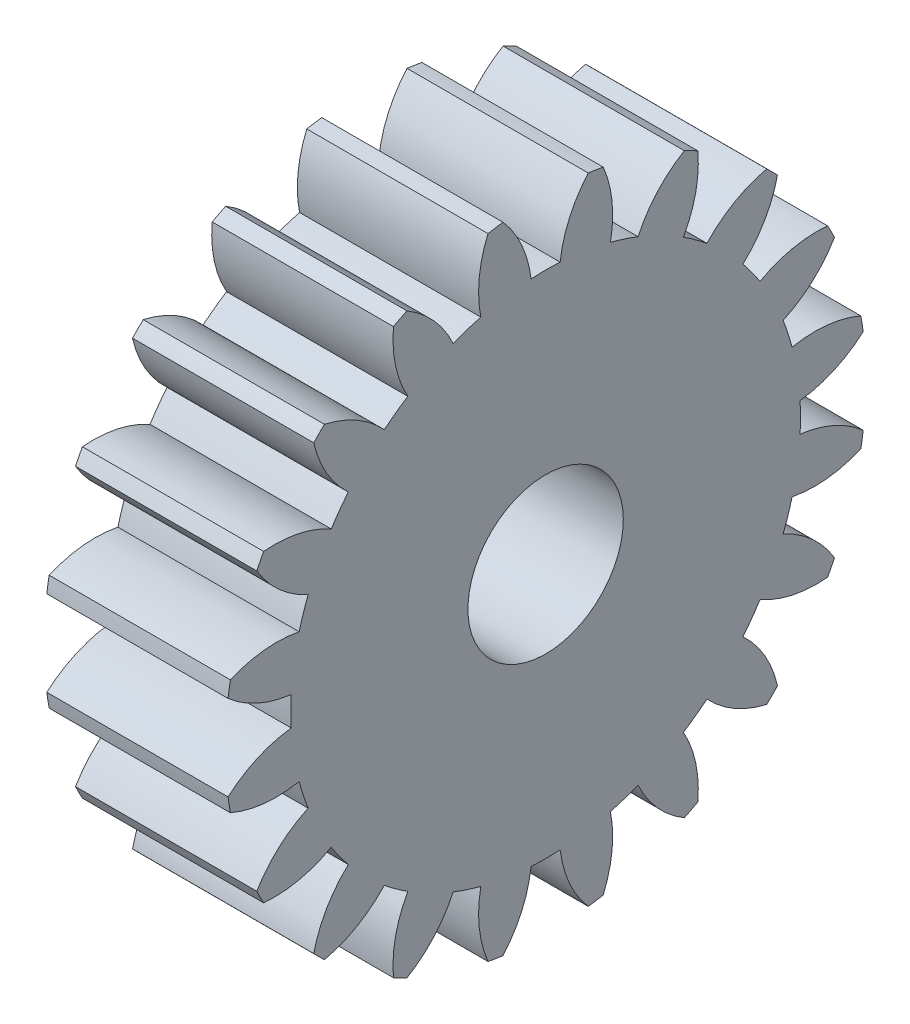
SolidWorks part; units mm, degrees
ref_plane "Plane1" through (0, 0, 0) normal (0, 0, 1) x (1, 0, 0)
ref_plane "Plane2" through (0, 0, 0) normal (0, 1, 0) x (1, 0, 0)
ref_plane "Plane3" through (0, 0, 0) normal (1, 0, 0) x (0, 0, -1)
sketch "HoldingSke" plane through (0, 0, 0) normal (0, 1, 0) x (1, 0, 0)
  line L0 (0, 0) -> (0.8353, -0.304)
  line L1 (-15, 0) -> (100, 0) construction
  line L2 (0, 0) -> (-2.1039, 2.3779)
  line L3 (0, 0) -> (-11.863, 4.5341)
  line L4 (0, 0) -> (8.1152, 2.9537)
  line L5 (0, 0) -> (-46.8476, -17.4728)
  line L6 (0, 0) -> (-4.9738, -3.3558)
  line L7 (-2.1039, 2.3779) -> (8.6586, 51.2059)
  line L8 (-76.2, 54.61) -> (-75.2, 54.61)
  line L9 (-71.009, 38.7566) -> (-53.1078, 45.2721)
  line L10 (-76.2, 71.12) -> (104.1128, 71.12)
  line L11 (0, 0) -> (-6, 0)
  line L12 (-76.2, 101.6) -> (-76.158, 101.6)
  line L13 (24.9733, 27.94) -> (52.9518, 28.4284)
  line L14 (24.9733, 27.94) -> (24.9743, 27.94)
  line L15 (24.9733, 27.94) -> (100.4006, 29.5858)
  line L16 (-63.627, -1.125) -> (-12.827, -1.125)
  circle A0 centre (0, 0) radius 3
  circle A1 centre (0, 0) radius 9.8427
  circle A2 centre (0, 0) radius 37.5
  circle A3 centre (0, 0) radius 3
  dimension "MHD" = 19.6855
  dimension "Hub_dia" = 75
  dimension "Bore" = 6
  dimension "MBD" = 6
  dimension "Num_teeth" = 20
  dimension "Pitch" = 0.8889
  dimension "Overall_len" = 50
  dimension "Show_teeth" = 20
  dimension "Thickness" = 6
  dimension "OAL" = 50.0001
  dimension "T_dim" = 1
  dimension "Ap" = 20
  dimension "H" = 19.05
  dimension "Pitch_radius" = 180.3128
  dimension "Width" = 6
  dimension "Backlash" = 0.042
  dimension "Addendum_fac" = 1
  dimension "Dedendum_fac" = 1.25
  dimension "Clearance_fac" = 0.25
  dimension "Dedendum_add" = 0.001
  dimension "Module" = 1.125
sketch "BasProSke" plane through (0, 0, 0) normal (0, 1, 0) x (1, 0, 0)
  line L0 (-10, 0) -> (60, 0) construction
  line L1 (0, 0) -> (0, 12.375)
  line L2 (0, 0) -> (7, 0)
  line L3 (7, 0) -> (7, 12.375)
  line L4 (7, 12.375) -> (0, 12.375)
  dimension "Thickness" = 7
  dimension "Diameter" = 24.75
revolve "Base-Revolve" add sketch "BasProSke" angle 360 about L0
sketch "TooCutSke" plane through (0, 0, 0) normal (1, 0, 0) x (0, 0, -1)
  line L1 (0, 0) -> (0, 107) construction
  line L2 (0, 0) -> (-0.9561, 11.2093) construction
  line L3 (0, 0) -> (-3.5107, 22.1654) construction
  line L4 (-0.9561, 11.2093) -> (-1.7553, 11.0827) construction
  arc A0 (0.5613, 9.8267) -> (-0.5613, 9.8267) centre (0, 0) ccw
  arc A1 (1.6669, 12.2879) -> (-1.6669, 12.2879) centre (0, 0) ccw
  circle A2 centre (0, 0) radius 11.25 construction
  circle A3 centre (0, 0) radius 10.5715 construction
  arc A4 (-0.5613, 9.8267) -> (-1.6669, 12.2879) centre (-5.0301, 9.2981) ccw
  arc A5 (1.6669, 12.2879) -> (0.5613, 9.8267) centre (5.0301, 9.2981) ccw
  dimension "Root_dia" = 19.6855
  dimension "Overcut_dia" = 24.8008
  dimension "Pitch_dia" = 22.5
  dimension "Base_dia" = 21.1431
  dimension "Flank_rad" = 4.5
  dimension "Half_ang" = 9
  dimension "Half_CT" = 0.8092
extrude "ToothCut" cut sketch "TooCutSke" along normal through all
fillet "Breaks" [suppressed] radius 0.0225
fillet "RootFillets" [suppressed] radius 0.2823
pattern_circular "TeethCuts" count 20 over 360 about axis through (0, 0, 0) along (1, 0, 0) of "ToothCut", "RootFillets", "Breaks"
sketch "HubNeaOneSke" plane through (0, 0, 0) normal (-1, 0, 0) x (0, 0, 1)
  circle A0 centre (0, 0) radius 9.8427
  dimension "Diameter" = 19.6855
extrude "HubNearOne" [suppressed] add sketch "HubNeaOneSke" along normal blind 43.0001
sketch "HubNeaBotSke" plane through (0, 0, 0) normal (-1, 0, 0) x (0, 0, 1)
  circle A0 centre (0, 0) radius 9.8427
  dimension "Diameter" = 19.6855
extrude "HubNearBoth" [suppressed] add sketch "HubNeaBotSke" along normal blind 21.5
ref_plane "FarPln" through (7, 0, 0) normal (1, 0, 0) x (0, 0, -1)
sketch "HubFarSke" plane through (7, 0, 0) normal (1, 0, 0) x (0, 0, -1)
  circle A0 centre (0, 0) radius 9.8427
  dimension "Diameter" = 19.6855
extrude "HubFar" [suppressed] add sketch "HubFarSke" along normal blind 21.5
sketch "BorSke" plane through (0, 0, 0) normal (1, 0, 0) x (0, 0, -1)
  circle A0 centre (0, 0) radius 3
  dimension "Diameter" = 6
extrude "Bore" cut sketch "BorSke" along normal mid plane 100.0001
sketch "KeySke" plane through (0, 0, 0) normal (1, 0, 0) x (0, 0, -1)
  line L0 (-1, 0) -> (-1, 4)
  line L1 (-1, 4) -> (1, 4)
  line L2 (1, 4) -> (1, 0)
  line L3 (0, 0) -> (0, 34) construction
  line L4 (-1, 0) -> (1, 0)
  dimension "Offset" = 4
  dimension "Width" = 2
extrude "Keyway" [suppressed] cut sketch "KeySke" along normal mid plane 100.0001
pattern_circular "Keyway2" [suppressed] count 2 every 90 about axis through (-10, 0, 0) along (1, 0, 0)
sketch "Sketch1" plane through (7, 0, 0) normal (1, 0, 0) x (0, 0, -1)
  circle A0 centre (0, 0) radius 3 construction
  circle A1 centre (0, 0) radius 3
extrude "Boss-Extrude1" add sketch "Sketch1" against normal up to surface (7 mm away) up to face at (0, 0, -3)
sketch "Sketch2" plane through (7, 0, 0) normal (1, 0, 0) x (0, 0, -1)
  line L0 (-1.8, 2.0125) -> (-1.8, -2.0125)
  line L1 (1.8, 2.0125) -> (1.8, -2.0125)
  line L2 (-1.8, 0) -> (1.8, 0) construction
  circle A0 centre (0, 0) radius 2.7
  point P9 (0, 0)
  dimension "D1" = 5.4
  dimension "D2" = 3.6
extrude "Cut-Extrude1" cut sketch "Sketch2" against normal up to surface (7 mm away) contours L0 L2 L1 A0 | L2 L0 A0 L1 up to face at (0, 0, 0)
sketch "Sketch3" plane through (7, 0, 0) normal (1, 0, 0) x (0, 0, -1)
  circle A0 centre (0, 0) radius 3
  dimension "D1" = 6
extrude "Cut-Extrude2" cut sketch "Sketch3" against normal up to surface (7 mm away) up to face at (0, 0, 0)
equation "' \"Module@HoldingSke\" = 6.35"
equation "' \"Num_teeth@HoldingSke\" = 12"
equation "' \"Ap@HoldingSke\" =  20"
equation "' \"Ap@HoldingSke\" = 20"
equation "' \"Width@HoldingSke\" = 0.5 * 25.4"
equation "' \"Hub_dia@HoldingSke\"= 1 * 25.4"
equation "' \"Hub_dia@HoldingSke\" = 1 * 25.4"
equation "' \"Overall_len@HoldingSke\" = 1.0 * 25.4"
equation "' \"Bore@HoldingSke\" = 0.75 * 25.4"
equation "' \"T_dim@HoldingSke\" = 0.1 * 25.4"
equation "' \"Width@KeySke\" = 0.25 * 25.4"
equation "' \"Show_teeth@HoldingSke\" = 13"
equation "' \"Backlash@HoldingSke\" = 0.009 * 25.4"
equation "' \"Addendum_fac@HoldingSke\" = 1.0"
equation "' \"Dedendum_fac@HoldingSke\" = 1.25"
equation "' \"Dedendum_add@HoldingSke\" = 0.00005 * 25.4"
equation "' \"Clearance_fac@HoldingSke\" = 0.25"
equation "\"Pitch@HoldingSke\" = 1 / \"Module@HoldingSke\""
equation "\"Overcut_dia@TooCutSke\" = (\"Num_teeth@HoldingSke\" + 2 * \"Addendum_fac@HoldingSke\") / \"Pitch@HoldingSke\" + 0.002 * 25.4"
equation "\"Pitch_dia@TooCutSke\" = \"Num_teeth@HoldingSke\" / \"Pitch@HoldingSke\""
equation "\"Base_dia@TooCutSke\" = \"Num_teeth@HoldingSke\" / \"Pitch@HoldingSke\" * cos((\"Ap@HoldingSke\"  * 3.14159265 / 180))"
equation "\"Root_dia@TooCutSke\" = (\"Num_teeth@HoldingSke\" + 2) / \"Pitch@HoldingSke\" - 2 * (\"Addendum_fac@HoldingSke\" + \"Dedendum_fac@HoldingSke\") / \"Pitch@HoldingSke\" - \"Dedendum_add@HoldingSke\" * 2"
equation "\"Half_ang@TooCutSke\" = 180 / \"Num_teeth@HoldingSke\""
equation "\"Half_CT@TooCutSke\" = \"Num_teeth@HoldingSke\" / \"Pitch@HoldingSke\" * sin((3.14159265 / 2 / \"Num_teeth@HoldingSke\")) / 2 - 7 * \"Backlash@HoldingSke\" / 4"
equation "\"Flank_rad@TooCutSke\" = \"Num_teeth@HoldingSke\" / \"Pitch@HoldingSke\" / 5"
equation "\"Radius@RootFillets\" = \"Clearance_fac@HoldingSke\" / \"Pitch@HoldingSke\" + \"Dedendum_add@HoldingSke\""
equation "\"Break_rad@Breaks\" = 0.02 / \"Pitch@HoldingSke\""
equation "\"Thickness@HoldingSke\" = \"Width@HoldingSke\""
equation "\"OAL@HoldingSke\" = \"Thickness@HoldingSke\""
equation "\"MHD@HoldingSke\" = (\"Num_teeth@HoldingSke\" + 2) / \"Pitch@HoldingSke\" - 2 * (\"Addendum_fac@HoldingSke\" + \"Dedendum_fac@HoldingSke\")  / \"Pitch@HoldingSke\" - \"Dedendum_add@HoldingSke\" * 2"
equation "\"MBD@HoldingSke\" = (\"Num_teeth@HoldingSke\" + 2) / \"Pitch@HoldingSke\" - 2 * (\"Addendum_fac@HoldingSke\" + \"Dedendum_fac@HoldingSke\")  / \"Pitch@HoldingSke\" - \"Dedendum_add@HoldingSke\" * 2 - 0.002 * 25.4"
equation "\"MHD@HoldingSke\" = ((sgn( \"MHD@HoldingSke\" - \"Hub_dia@HoldingSke\" )-1)*( \"MHD@HoldingSke\" - \"Hub_dia@HoldingSke\" ))/-2+ \"Hub_dia@HoldingSke\""
equation "\"MBD@HoldingSke\" = ((sgn( \"MBD@HoldingSke\" - \"Bore@HoldingSke\" )-1)*( \"MBD@HoldingSke\" - \"Bore@HoldingSke\" ))/-2+ \"Bore@HoldingSke\""
equation "\"OAL@HoldingSke\" = ((sgn( \"OAL@HoldingSke\" - \"Overall_len@HoldingSke\" )+1)*( \"OAL@HoldingSke\" - \"Overall_len@HoldingSke\" ))/2 + \"Overall_len@HoldingSke\" + 0.000002 * 25.4"
equation "\"Num_teeth@TeethCuts\" = int( \"Show_teeth@HoldingSke\" ) + 1"
equation "\"Num_teeth@TeethCuts\" = ((sgn( \"Num_teeth@TeethCuts\" - \"Num_teeth@HoldingSke\" )-1)*( \"Num_teeth@TeethCuts\" - \"Num_teeth@HoldingSke\" ))/-2+ \"Num_teeth@HoldingSke\""
equation "\"Num_teeth@TeethCuts\" = ((sgn( \"Num_teeth@TeethCuts\" - 2.0)+1)*( \"Num_teeth@TeethCuts\" - 2.0))/2 +2.0"
equation "\"Angle@TeethCuts\" = 360.0 / \"Num_teeth@HoldingSke\""
equation "\"Diameter@BasProSke\" = (\"Num_teeth@HoldingSke\" + 2 * \"Addendum_fac@HoldingSke\") / \"Pitch@HoldingSke\""
equation "' \"Fillet_rad@BasProSke\" =  \"Thickness@HoldingSke\" * 0.05"
equation "' \"Fillet_rad@BasProSke\" = \"Thickness@HoldingSke\" * 0.05"
equation "\"MHD@HoldingSke\" = ((sgn( \"MHD@HoldingSke\" - \"Root_dia@TooCutSke\" )-1)*( \"MHD@HoldingSke\" - \"Root_dia@TooCutSke\" ))/-2+ \"Root_dia@TooCutSke\""
equation "\"Diameter@HubNeaOneSke\" = \"MHD@HoldingSke\""
equation "\"Length@HubNearOne\" = \"OAL@HoldingSke\" - \"Thickness@BasProSke\""
equation "\"Diameter@HubNeaBotSke\" = \"MHD@HoldingSke\""
equation "\"Length@HubNearBoth\" = ( \"OAL@HoldingSke\" - \"Thickness@BasProSke\" ) / 2.0"
equation "\"Thickness@FarPln\" = \"Thickness@BasProSke\""
equation "\"Diameter@HubFarSke\" = \"MHD@HoldingSke\""
equation "\"Length@HubFar\" = ( \"OAL@HoldingSke\" - \"Thickness@BasProSke\" ) / 2.0"
equation "\"Diameter@BorSke\" = \"MBD@HoldingSke\""
equation "\"D1@Bore\" = \"OAL@HoldingSke\" * 2.0"
equation "\"D1@Keyway\" = \"OAL@HoldingSke\" * 2.0"
equation "\"Offset@KeySke\" = \"T_dim@HoldingSke\" + \"MBD@HoldingSke\" / 2.0"
